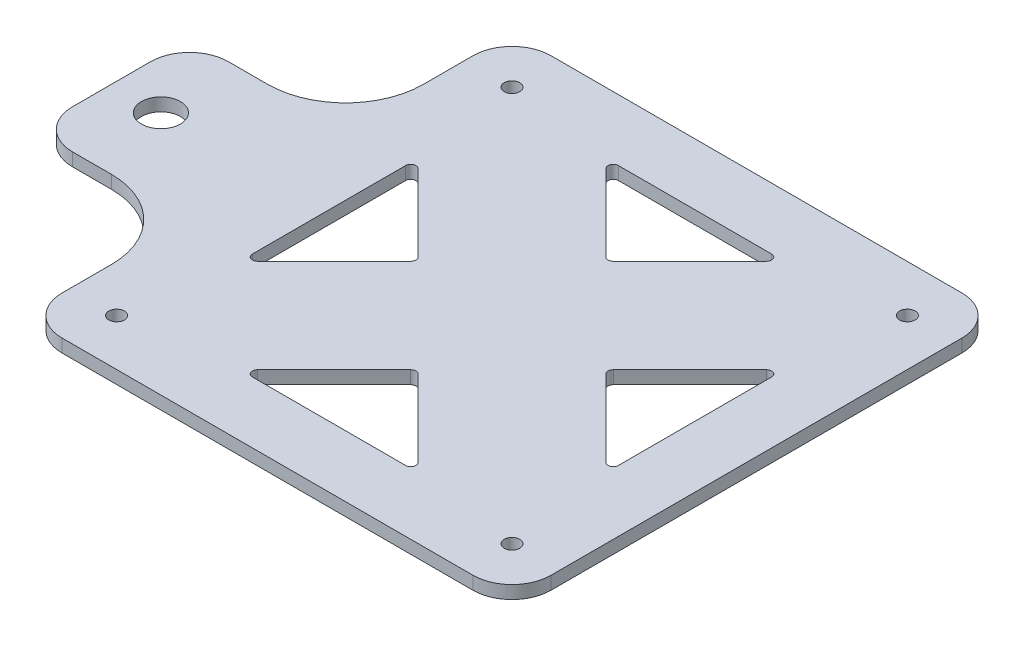
SolidWorks part; units mm, degrees
material "1060 Alloy"
ref_plane "Front Plane" through (0, 0, 0) normal (0, 0, 1) x (1, 0, 0)
ref_plane "Top Plane" through (0, 0, 0) normal (0, 1, 0) x (1, 0, 0)
ref_plane "Right Plane" through (0, 0, 0) normal (1, 0, 0) x (0, 0, -1)
sketch "Sketch1" plane through (0, 0, 0) normal (0, 1, 0) x (1, 0, 0)
  line L2 (-70.3845, -51.1373) -> (70.3845, 51.1373) construction
  line L3 (-79, 94) -> (79, 94)
  line L4 (-94, 79) -> (-94, 30)
  line L11 (-79, -94) -> (79, -94)
  line L12 (94, 79) -> (94, -79)
  line L13 (-94, 94) -> (94, -94) construction
  line L14 (-94, -94) -> (94, 94) construction
  line L15 (51.1373, 70.3845) -> (-51.1373, -70.3845) construction
  line L16 (-94, -30) -> (-154, -30)
  line L17 (-154, -30) -> (-154, 30)
  line L18 (-154, 30) -> (-94, 30)
  line L19 (-94, -30) -> (-94, -79)
  line L20 (29.4468, -70.3845) -> (-29.4468, -70.3845)
  line L21 (-30.861, -66.9703) -> (-1.4142, -37.5235)
  line L22 (1.4142, -37.5235) -> (30.861, -66.9703)
  line L23 (-70.3845, -29.4468) -> (-70.3845, 29.4468)
  line L24 (-66.9703, 30.861) -> (-37.5235, 1.4142)
  line L25 (-37.5235, -1.4142) -> (-66.9703, -30.861)
  line L26 (-29.4468, 70.3845) -> (29.4468, 70.3845)
  line L27 (30.861, 66.9703) -> (1.4142, 37.5235)
  line L28 (-1.4142, 37.5235) -> (-30.861, 66.9703)
  line L29 (70.3845, 29.4468) -> (70.3845, -29.4468)
  line L30 (66.9703, -30.861) -> (37.5235, -1.4142)
  line L31 (37.5235, 1.4142) -> (66.9703, 30.861)
  circle A37 centre (0, 0) radius 107.5 construction
  circle A38 centre (-76.014, 76.014) radius 3
  circle A39 centre (76.014, 76.014) radius 3
  circle A40 centre (76.014, -76.014) radius 3
  circle A41 centre (-76.014, -76.014) radius 3
  circle A42 centre (0, 0) radius 94 construction
  circle A43 centre (0, 0) radius 87 construction
  circle A44 centre (-70.3845, -51.1373) radius 2 construction
  circle A45 centre (51.1373, 70.3845) radius 2 construction
  circle A46 centre (70.3845, 51.1373) radius 2 construction
  circle A47 centre (-51.1373, -70.3845) radius 2 construction
  arc A48 (94, 79) -> (79, 94) centre (79, 79) ccw
  arc A49 (94, -79) -> (79, -94) centre (79, -79) cw
  arc A50 (-79, -94) -> (-94, -79) centre (-79, -79) cw
  arc A51 (-94, 79) -> (-79, 94) centre (-79, 79) cw
  circle A52 centre (-135, 0) radius 7.5
  circle A53 centre (-135, 0) radius 10 construction
  circle A54 centre (-135, -10) radius 1.5 construction
  circle A55 centre (-145, 0) radius 1.5 construction
  circle A56 centre (-135, 10) radius 1.5 construction
  circle A57 centre (-125, 0) radius 1.5 construction
  circle A58 centre (-135, 10) radius 3.5 construction
  circle A59 centre (-135, 0) radius 9.5 construction
  arc A60 (-37.5235, -1.4142) -> (-37.5235, 1.4142) centre (-38.9377, 0) ccw
  arc A61 (-70.3845, 29.4468) -> (-66.9703, 30.861) centre (-68.3845, 29.4468) cw
  arc A62 (-70.3845, -29.4468) -> (-66.9703, -30.861) centre (-68.3845, -29.4468) ccw
  arc A63 (29.4468, 70.3845) -> (30.861, 66.9703) centre (29.4468, 68.3845) cw
  arc A64 (-29.4468, 70.3845) -> (-30.861, 66.9703) centre (-29.4468, 68.3845) ccw
  arc A65 (-1.4142, 37.5235) -> (1.4142, 37.5235) centre (0, 38.9377) ccw
  arc A66 (66.9703, 30.861) -> (70.3845, 29.4468) centre (68.3845, 29.4468) cw
  arc A67 (66.9703, -30.861) -> (70.3845, -29.4468) centre (68.3845, -29.4468) ccw
  arc A68 (37.5235, 1.4142) -> (37.5235, -1.4142) centre (38.9377, 0) ccw
  arc A69 (-30.861, -66.9703) -> (-29.4468, -70.3845) centre (-29.4468, -68.3845) ccw
  arc A70 (30.861, -66.9703) -> (29.4468, -70.3845) centre (29.4468, -68.3845) cw
  arc A71 (-1.4142, -37.5235) -> (1.4142, -37.5235) centre (0, -38.9377) cw
  point P0 (0, 0)
  point P26 (0, 0)
  point P28 (0, 0)
  point P31 (-154, 0)
  point P60 (-135, 0)
  point P64 (0, -70.3845)
  point P75 (0, 0)
  point P100 (0, -36.1093)
  dimension "D1" = 215
  dimension "D2" = 6
  dimension "D4" = 174
  dimension "D5" = 4
  dimension "D6" = 18
  dimension "D8" = 15
  dimension "D9" = 60
  dimension "D11" = 15
  dimension "D12" = 20
  dimension "D13" = 3
  dimension "D14" = 4
  dimension "D10" = 60
  dimension "D15" = 7
  dimension "D7" = 9
  dimension "D3" = 188
  dimension "D16" = 2
  dimension "D19" = 2
  dimension "D17" = 135
  dimension "D18" = 4
extrude "Boss-Extrude1" add sketch "Sketch1" along normal mid plane 5
fillet "Fillet1" radius 30 2 edges at (-94, 0, 30) (-94, 0, -30)
fillet "Fillet2" radius 15 2 edges at (-154, 0, -30) (-154, 0, 30)
